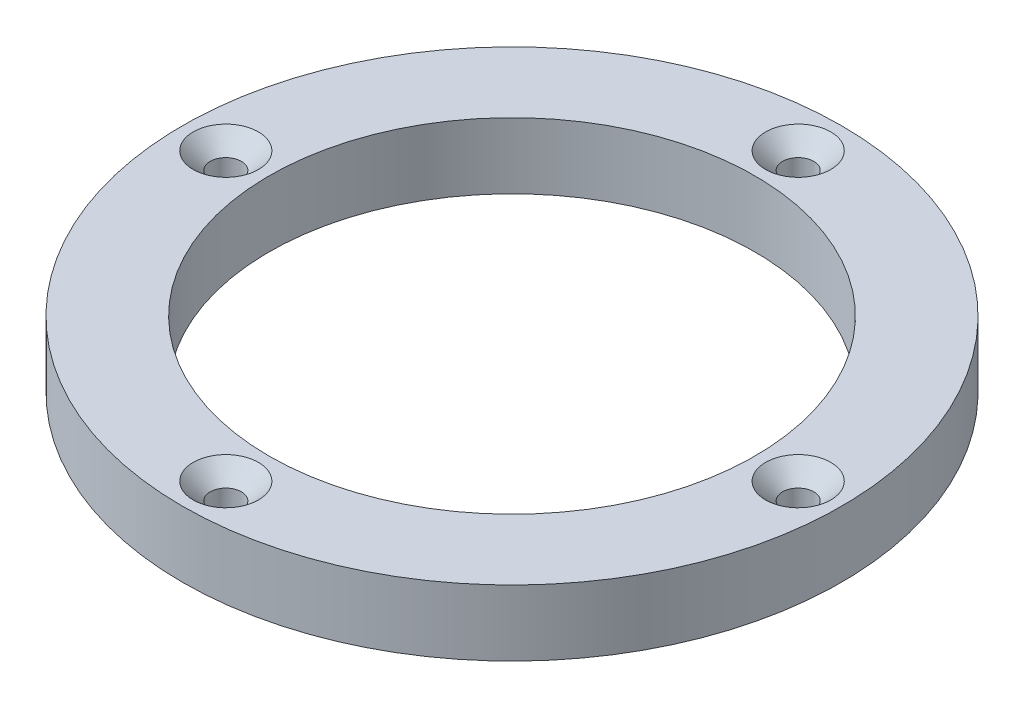
SolidWorks part; units mm, degrees
ref_plane "Front Plane" through (0, 0, 0) normal (0, 0, 1) x (1, 0, 0)
ref_plane "Top Plane" through (0, 0, 0) normal (0, 1, 0) x (1, 0, 0)
ref_plane "Right Plane" through (0, 0, 0) normal (1, 0, 0) x (0, 0, -1)
sketch "Sketch1" plane through (0, 0, 0) normal (0, 1, 0) x (1, 0, 0)
  circle A0 centre (0, 0) radius 47.5
  circle A1 centre (0, 0) radius 35
  dimension "D1" = 95
  dimension "D2" = 70
extrude "Boss-Extrude1" add sketch "Sketch1" along normal blind 9.5
sketch "Sketch2" plane through (0, 9.5, 0) normal (0, 1, 0) x (1, 0, 0)
  line L0 (-68.1724, 0) -> (77.449, 0) construction
  line L1 (0, 71.0864) -> (0, -90.573) construction
  circle A0 centre (0, 0) radius 35 construction
  circle A1 centre (0, 0) radius 47.5 construction
  circle A2 centre (0, 41.25) radius 2.25
  circle A3 centre (41.25, 0) radius 2.25
  circle A4 centre (0, -41.25) radius 2.25
  circle A5 centre (-41.25, 0) radius 2.25
  point P5 (0, 35)
  point P6 (0, 47.5)
  point P9 (35, 0)
  point P12 (47.5, 0)
  dimension "D2" = 4.5
  dimension "D4" = 4.5
  dimension "D1" = 6.25
  dimension "D3" = 6.25
extrude "Cut-Extrude1" cut sketch "Sketch2" against normal blind 10
hole_wizard "CSK for M4 Countersunk Flat Head Screw1" positions "3DSketch2" profile "Sketch3" countersink size "M4" standard "ISO" end condition through all
sketch3d "3DSketch2"
  line L0 (0, 0, 41.25) -> (0, 9.5, 41.25) construction
  line L1 (41.25, 0, 0) -> (41.25, 9.5, 0) construction
  line L2 (0, 0, -41.25) -> (0, 9.5, -41.25) construction
  line L3 (-41.25, 0, 0) -> (-41.25, 9.5, 0) construction
  point P0 (0, 9.5, 41.25)
  point P4 (41.25, 9.5, 0)
  point P8 (0, 9.5, -41.25)
  point P12 (-41.25, 9.5, 0)
sketch "Sketch3" plane through (0, 9.5, 41.25) normal (1, 0, 0) x (0, 0, 1)
  line L0 (0, 0) -> (0, 9.5)
  line L1 (0, 9.5) -> (2.25, 9.5)
  line L2 (2.25, 9.5) -> (2.25, 2.45)
  line L3 (2.25, 2.45) -> (4.7, 0)
  line L5 (4.7, 0) -> (0, 0)
  line L6 (-2.25, 2.45) -> (-4.7, 0) construction
  line L11 (0, -6.35) -> (0, 107.95) construction
  dimension "Thru Hole Dia." = 4.5
  dimension "Thru Hole Depth" = 9.5
  dimension "Near C'Sink Dia." = 9.4
  dimension "Near C'Sink Angle" = 90
